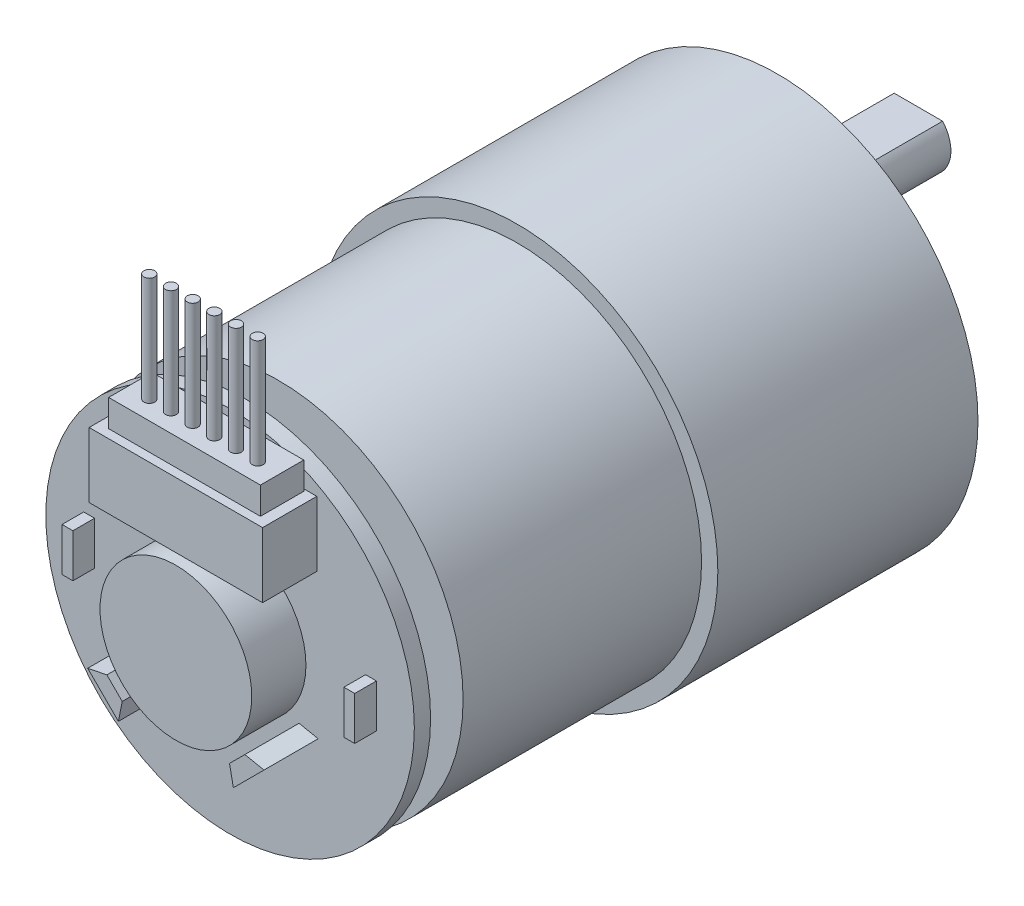
SolidWorks part; units mm, degrees
ref_plane "Front" through (0, 0, 0) normal (0, 0, 1) x (1, 0, 0)
ref_plane "Top" through (0, 0, 0) normal (0, 1, 0) x (1, 0, 0)
ref_plane "Right" through (0, 0, 0) normal (1, 0, 0) x (0, 0, -1)
sketch "草图1" plane through (0, 0, 0) normal (0, 0, 1) x (1, 0, 0)
  circle A0 centre (0, 0) radius 18.5
  dimension "D1" = 37
extrude "凸台-拉伸1" add sketch "草图1" along normal blind 24
sketch "草图2" plane through (0, 0, 24) normal (0, 0, 1) x (1, 0, 0)
  circle A0 centre (0, 0) radius 17
  dimension "D1" = 34
extrude "凸台-拉伸2" add sketch "草图2" along normal blind 22
sketch "草图3" plane through (0, 0, 46) normal (0, 0, 1) x (1, 0, 0)
  line L1 (-12.5, -1.5) -> (-13, -1.5)
  line L2 (-12.5, -1.5) -> (-12.5, 1.5)
  line L3 (-12.5, 1.5) -> (-13, 1.5)
  line L4 (-13, -1.5) -> (-13, 1.5)
  line L5 (-12.5, -1.5) -> (-13, 1.5) construction
  line L6 (-12.5, 1.5) -> (-13, -1.5) construction
  line L7 (13, -1.5) -> (12.5, -1.5)
  line L8 (13, -1.5) -> (13, 1.5)
  line L9 (13, 1.5) -> (12.5, 1.5)
  line L10 (12.5, -1.5) -> (12.5, 1.5)
  line L11 (13, -1.5) -> (12.5, 1.5) construction
  line L12 (13, 1.5) -> (12.5, -1.5) construction
  circle A0 centre (0, 0) radius 3
  point P0 (-12.75, 0)
  point P5 (12.75, 0)
  dimension "D1" = 0.5
  dimension "D2" = 3
  dimension "D3" = 0.5
  dimension "D4" = 3
  dimension "D5" = 12.5
  dimension "D6" = 12.5
  dimension "D7" = 0
  dimension "D8" = 0
extrude "凸台-拉伸3" add sketch "草图3" along normal blind 3
sketch "草图4" plane through (0, 0, 49) normal (0, 0, 1) x (1, 0, 0)
  circle A0 centre (0, 0) radius 17
extrude "凸台-拉伸4" add sketch "草图4" along normal blind 1.5
sketch "草图5" plane through (0, 0, 50.5) normal (0, 0, 1) x (1, 0, 0)
  line L5 (-5.6569, -5.6569) -> (-6.364, -4.9497)
  line L9 (-4.9497, -6.364) -> (-5.6569, -5.6569)
  line L11 (-6.7175, -6.7175) -> (-8.1317, -5.3033)
  line L12 (-6.7175, -6.7175) -> (-5.3033, -8.1317)
  line L13 (-8.1317, -5.3033) -> (-6.364, -4.9497)
  line L14 (-4.9497, -6.364) -> (-5.3033, -8.1317)
  line L15 (5.6569, -5.6569) -> (6.364, -4.9497)
  line L16 (5.6569, -5.6569) -> (4.9497, -6.364)
  line L18 (6.7175, -6.7175) -> (8.1317, -5.3033)
  line L19 (6.7175, -6.7175) -> (5.3033, -8.1317)
  line L20 (5.3033, -8.1317) -> (4.9497, -6.364)
  line L21 (6.364, -4.9497) -> (8.1317, -5.3033)
  circle A0 centre (0, 0) radius 7
  dimension "D3" = 1.5
  dimension "D4" = 1
  dimension "D5" = 2
  dimension "D6" = 1
  dimension "D7" = 2
extrude "凸台-拉伸5" add sketch "草图5" along normal blind 5
sketch "草图6" plane through (0, 0, 50.5) normal (0, 0, 1) x (1, 0, 0)
  line L1 (-13.5, 2) -> (-12.5, 2)
  line L2 (-13.5, 2) -> (-13.5, -2)
  line L3 (-13.5, -2) -> (-12.5, -2)
  line L4 (-12.5, 2) -> (-12.5, -2)
  line L5 (12.5, 2) -> (13.5, 2)
  line L6 (12.5, 2) -> (12.5, -2)
  line L7 (12.5, -2) -> (13.5, -2)
  line L8 (13.5, 2) -> (13.5, -2)
  point P8 (-12.5, 0)
  point P10 (12.5, 0)
  dimension "D1" = 12.5
  dimension "D2" = 12.5
  dimension "D3" = 1
  dimension "D4" = 1
  dimension "D5" = 4
  dimension "D6" = 4
  dimension "D7" = 0
  dimension "D8" = 0
extrude "凸台-拉伸6" add sketch "草图6" along normal blind 2
sketch "草图7" plane through (0, 0, 50.5) normal (0, 0, 1) x (1, 0, 0)
  line L1 (-8, 14) -> (8, 14)
  line L2 (-8, 14) -> (-8, 8)
  line L3 (-8, 8) -> (8, 8)
  line L4 (8, 14) -> (8, 8)
  circle A0 centre (0, 0) radius 7 construction
  point P4 (0, 8)
  dimension "D1" = 16
  dimension "D2" = 6
  dimension "D3" = 0
  dimension "D4" = 8
extrude "凸台-拉伸7" add sketch "草图7" along normal blind 5
sketch "草图8" plane through (0, 14, 0) normal (0, 1, 0) x (1, 0, 0)
  line L0 (8, -55.5) -> (-8, -55.5) construction
  line L1 (7, -54.7) -> (-7, -54.7)
  line L2 (7, -54.7) -> (7, -50.7)
  line L3 (7, -50.7) -> (-7, -50.7)
  line L4 (-7, -54.7) -> (-7, -50.7)
  line L5 (8, -55.5) -> (8, -50.5) construction
  dimension "D1" = 4
  dimension "D2" = 14
  dimension "D3" = 0.8
  dimension "D4" = 1
extrude "凸台-拉伸8" add sketch "草图8" along normal blind 2.5
sketch "草图9" plane through (0, 16.5, 0) normal (0, 1, 0) x (1, 0, 0)
  line L0 (-7, -54.7) -> (7, -54.7) construction
  line L1 (7, -54.7) -> (7, -50.7) construction
  circle A0 centre (5, -52.95) radius 0.5
  dimension "D1" = 2
  dimension "1.76" = 1.75
extrude "凸台-拉伸9" add sketch "草图9" along normal blind 10
pattern_linear "阵列(线性)1" count 6 spacing 2 along (-1, 0, 0) of "凸台-拉伸9"
sketch "草图13" plane through (0, 0, 0) normal (0, 0, -1) x (-1, 0, 0)
  line L0 (0, 0) -> (18.4959, -0.39)
  line L1 (0, 0) -> (-12.5793, 0.2652)
  line L2 (0, 0) -> (0.39, 18.4959)
  line L3 (0, 0) -> (-0.39, -18.4959)
  circle A0 centre (0, 0) radius 18.5 construction
  circle A1 centre (-15.9964, 0.3373) radius 2
  circle A2 centre (8.0394, 13.8336) radius 2
  circle A3 centre (7.4491, -14.1602) radius 2
  circle A4 centre (-12.6713, 9.7693) radius 2
  circle A6 centre (-13.0718, -9.2265) radius 2
  circle A7 centre (0, 0) radius 16
  dimension "D1" = 16
  dimension "D2" = 16
  dimension "D3" = 16
  dimension "D4" = 14
  dimension "D5" = 14
  dimension "D6" = 16
  dimension "D7" = 16
  dimension "D8" = 9.5
  dimension "D9" = 9.5
  dimension "D10" = 90
  dimension "D11" = 90
sketch "草图11" plane through (0, 0, 0) normal (0, 0, -1) x (-1, 0, 0)
  line L0 (0, 0) -> (18.4959, -0.39) construction
  circle A1 centre (7.4983, -0.1581) radius 5.5
  dimension "D2" = 7.5
extrude "凸台-拉伸10" add sketch "草图11" along normal blind 5.5
sketch "草图10" plane through (0, 0, 0) normal (0, 0, -1) x (-1, 0, 0)
  arc A2 (10.0365, 6.3655) -> (9.7593, -6.7829) centre (0, 0) ccw
  arc A3 (10.0365, 6.3655) -> (9.7593, -6.7829) centre (7.4983, -0.1581) ccw
sketch "草图12" plane through (0, 0, -5.5) normal (0, 0, -1) x (-1, 0, 0)
  line L0 (5.2623, 1.8419) -> (9.7344, 1.8419)
  arc A1 (5.2623, 1.8419) -> (9.7344, 1.8419) centre (7.4983, -0.1581) ccw
  dimension "D1" = 2
  dimension "D2" = 6
extrude "凸台-拉伸11" add sketch "草图12" along normal blind 15
extrude "切除-拉伸2" cut sketch "草图10" against normal blind 0.4
sketch "草图14" plane through (0, 0, 0) normal (0, 0, -1) x (-1, 0, 0)
  circle A0 centre (8.0394, 13.8336) radius 2
  circle A1 centre (7.4491, -14.1602) radius 2
  circle A2 centre (-15.9964, 0.3373) radius 2
extrude "切除-拉伸3" cut sketch "草图14" against normal blind 0.5
sketch "草图15" plane through (0, 0, 0) normal (0, 0, -1) x (-1, 0, 0)
  line L0 (0, 0) -> (-0.39, -18.4959) construction
  line L1 (0, 0) -> (0.39, 18.4959) construction
  circle A2 centre (-0.3373, -15.9964) radius 2
  circle A3 centre (0, 0) radius 16 construction
  circle A4 centre (0.3373, 15.9964) radius 2
  circle A5 centre (-14.022, -7.7061) radius 2
  circle A6 centre (-13.6847, 8.2903) radius 2
  circle A7 centre (13.6847, -8.2903) radius 2
  circle A8 centre (14.022, 7.7061) radius 2
  dimension "D1" = 60
  dimension "D2" = 60
  dimension "D3" = 60
  dimension "D4" = 60
extrude "切除-拉伸4" cut sketch "草图15" against normal blind 3
